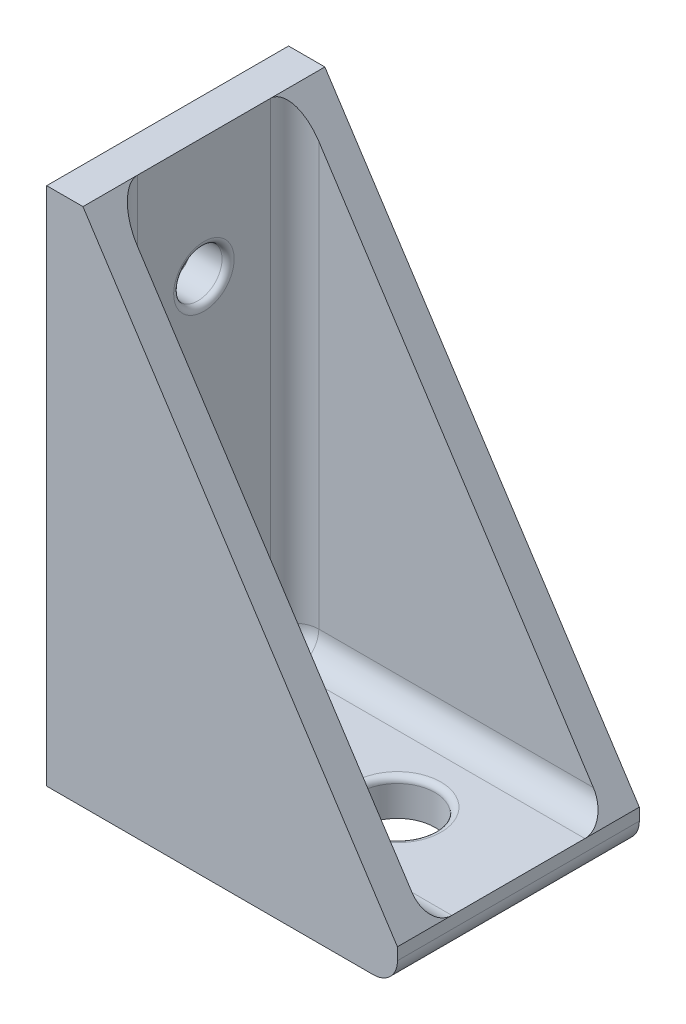
SolidWorks part; units mm, degrees
ref_plane "Front Plane" through (0, 0, 0) normal (0, 0, 1) x (1, 0, 0)
ref_plane "Top Plane" through (0, 0, 0) normal (0, 1, 0) x (1, 0, 0)
ref_plane "Right Plane" through (0, 0, 0) normal (1, 0, 0) x (0, 0, -1)
sketch "Sketch1" plane through (0, 0, 0) normal (0, 0, 1) x (1, 0, 0)
  line L0 (0, 43) -> (0, 0)
  line L1 (0, 0) -> (29, 0)
  line L2 (29, 0) -> (29, 3)
  line L3 (29, 3) -> (3, 3)
  line L4 (3, 3) -> (3, 43)
  line L5 (3, 43) -> (0, 43)
  dimension "D1" = 29
  dimension "D2" = 40
  dimension "D3" = 3
  dimension "D4" = 3
extrude "Boss-Extrude1" add sketch "Sketch1" along normal blind 20
sketch "Sketch2" plane through (0, 0, 20) normal (0, 0, 1) x (1, 0, 0)
  line L0 (3, 43) -> (29, 3)
  line L1 (29, 3) -> (3, 3)
  line L2 (3, 3) -> (3, 43)
extrude "Boss-Extrude2" add sketch "Sketch2" against normal blind 2.5
sketch "Sketch3" plane through (0, 0, 0) normal (0, 0, -1) x (-1, 0, 0)
  line L0 (-3, 43) -> (-29, 3)
  line L1 (-29, 3) -> (-3, 43) construction
  line L2 (-29, 3) -> (-3, 3)
  line L3 (-3, 3) -> (-3, 43)
extrude "Boss-Extrude3" add sketch "Sketch3" against normal blind 2.5
sketch "Sketch4" plane through (3, 0, 0) normal (1, 0, 0) x (0, 0, -1)
  line L0 (-10, 43) -> (-10, 3) construction
  line L1 (-17.5, 43) -> (-2.5, 43) construction
  line L2 (-17.5, 3) -> (-2.5, 3) construction
  circle A0 centre (-10, 33) radius 2
  circle A1 centre (-10, 13) radius 2
  dimension "D1" = 4
  dimension "D2" = 4
  dimension "D3" = 10
  dimension "D4" = 10
extrude "Cut-Extrude1" cut sketch "Sketch4" against normal through all
sketch "Sketch6" plane through (0, 0, 0) normal (0, -1, 0) x (1, 0, 0)
  line L0 (0, 10) -> (29, 10) construction
  line L1 (0, 20) -> (0, 0) construction
  line L2 (29, 20) -> (29, 0) construction
  circle A0 centre (19, 10) radius 3.1
  dimension "D1" = 6.2
  dimension "D2" = 19
extrude "Cut-Extrude2" cut sketch "Sketch6" against normal through all
fillet "Fillet1" radius 2 6 edges at (29, 0, 10) (16, 3, 17.5) (3, 23, 17.5) (3, 23, 2.5) (16, 3, 2.5) (3, 3, 10)
fillet "Fillet2" radius 0.5 3 edges at (3, 35, 10) (3, 15, 10) (22.1, 3, 10)
